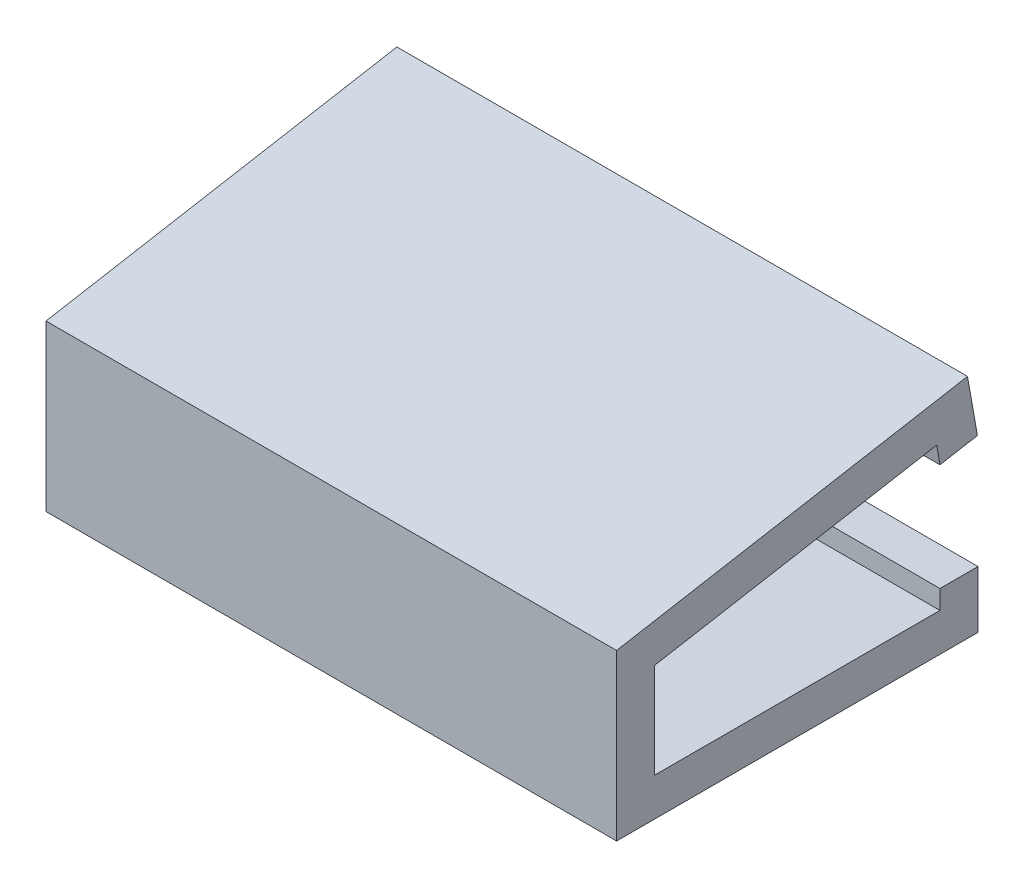
SolidWorks part; units mm, degrees
ref_plane "Front Plane" through (0, 0, 0) normal (0, 0, 1) x (1, 0, 0)
ref_plane "Top Plane" through (0, 0, 0) normal (0, 1, 0) x (1, 0, 0)
ref_plane "Right Plane" through (0, 0, 0) normal (1, 0, 0) x (0, 0, -1)
sketch "Sketch2" plane through (0, 0, 0) normal (1, 0, 0) x (0, 0, -1)
  line L0 (54.0603, 3.3334) -> (54.0603, -11.6666)
  line L1 (54.0603, -11.6666) -> (-40.9397, -11.6666)
  line L2 (-40.9397, -11.6666) -> (-40.9397, 31.7244)
  line L3 (-40.9397, 31.7244) -> (51.3036, 47.9894)
  line L4 (51.3036, 47.9894) -> (53.9083, 33.2173)
  line L5 (53.9083, 33.2173) -> (44.0603, 31.4808)
  line L6 (44.0603, 31.4808) -> (43.192, 36.4048)
  line L7 (43.192, 36.4048) -> (-30.9397, 23.3334)
  line L8 (-30.9397, 23.3334) -> (-30.9397, -1.6666)
  line L9 (-30.9397, -1.6666) -> (44.0603, -1.6666)
  line L10 (44.0603, -1.6666) -> (44.0603, 3.3334)
  line L11 (44.0603, 3.3334) -> (54.0603, 3.3334)
  line L12 (-30.9397, 23.3334) -> (39.0352, 23.3334) construction
  line L13 (-40.9397, 10.0289) -> (-30.9397, 10.0289) construction
  line L14 (5.1819, 39.8569) -> (6.9184, 30.0088) construction
  line L15 (6.5603, -1.6666) -> (6.5603, -11.6666) construction
  point P21 (34.9231, 21.4422)
  dimension "D1" = 10
  dimension "D2" = 25
  dimension "D7" = 75
  dimension "D3" = 10
  dimension "D4" = 5
extrude "Boss-Extrude1" add sketch "Sketch2" along normal blind 150
equation "\"WedgeInnerHeight\"=25"
equation "\"D2@Sketch2\"=\"WedgeInnerHeight\""
equation "\"WedgeThickness\"=10"
equation "\"D3@Sketch2\"=\"WedgeThickness\""
equation "\"RetainingLip\"=5"
equation "\"D4@Sketch2\"=\"RetainingLip\""
equation "\"WedgeLength\"= 150"
equation "\"D1@Boss-Extrude1\"=\"WedgeLength\""
equation "\"WedgeDepth\"= 75"
equation "\"D7@Sketch2\"=\"WedgeDepth\""
